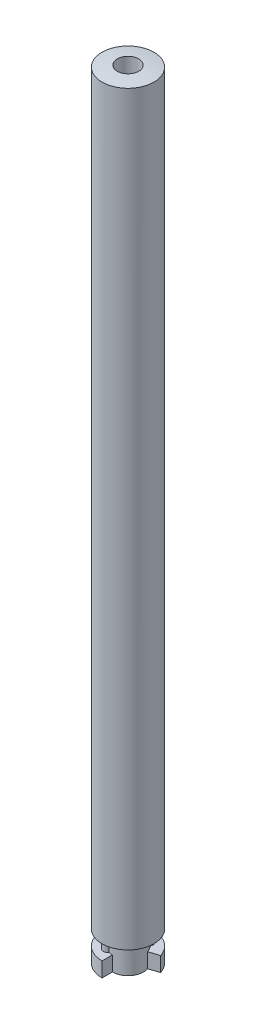
SolidWorks part; units mm, degrees
ref_plane "前视基准面" through (0, 0, 0) normal (0, 0, 1) x (1, 0, 0)
ref_plane "上视基准面" through (0, 0, 0) normal (0, 1, 0) x (1, 0, 0)
ref_plane "右视基准面" through (0, 0, 0) normal (1, 0, 0) x (0, 0, -1)
sketch "草图1" plane through (0, 0, 0) normal (0, 1, 0) x (1, 0, 0)
  circle A0 centre (0, 0) radius 3.5
  dimension "D1" = 7
extrude "凸台-拉伸1" add sketch "草图1" along normal blind 105
sketch "草图2" plane through (0, 0, 0) normal (0, -1, 0) x (1, 0, 0)
  line L0 (0, 0) -> (0, 3.5)
  line L1 (0, 0) -> (3.3287, -1.0816)
  line L2 (0, 3.5) -> (0, 2.1)
  line L3 (0, 0) -> (-3.3287, 1.0816)
  line L4 (0, 0) -> (0, -3.5)
  circle A0 centre (0, 0) radius 3.5 construction
  arc A1 (0, 3.5) -> (3.3287, -1.0816) centre (0, 0) cw
  arc A2 (1.9972, -0.6489) -> (0, 2.1) centre (0, 0) ccw
  arc A3 (0, -3.5) -> (-3.3287, 1.0816) centre (0, 0) cw
  arc A4 (-1.9972, 0.6489) -> (0, -2.1) centre (0, 0) ccw
  point P16 (0, 0)
  circle M1 centre (0, 0) radius 3.5
  dimension "D1" = 108
  dimension "D2" = 1.4
  dimension "D3" = 2
extrude "切除-拉伸1" cut sketch "草图2" against normal blind 2 contours A2 L1 L0 M1 | A4 L3 L4 M1
sketch "草图3" plane through (0, 2, 0) normal (0, -1, 0) x (1, 0, 0)
  circle A0 centre (0, 0) radius 3.5
  circle A1 centre (0, 0) radius 2.1
extrude "切除-拉伸3" cut sketch "草图3" against normal blind 2
sketch "草图4" plane through (0, 2, 0) normal (0, 1, 0) x (1, 0, 0)
  line L0 (-0.5435, -2.0284) -> (-0.9059, -3.3807) construction
  line L2 (0, -3.5) -> (0, -2.1)
  line L3 (-1.9972, -0.6489) -> (-3.3287, -1.0816)
  line L4 (0, -3.5) -> (0, -2.1)
  line L5 (-1.9972, -0.6489) -> (-3.3287, -1.0816)
  circle A0 centre (-0.5435, -2.0284) radius 0.5482 construction
  circle A1 centre (-1.026, -1.7681) radius 0.5482
  arc A2 (-3.3287, -1.0816) -> (0, -3.5) centre (0, 0) ccw
  arc A3 (-1.9972, -0.6489) -> (0, -2.1) centre (0, 0) ccw
  arc A4 (-3.3287, -1.0816) -> (0, -3.5) centre (0, 0) ccw
  arc A5 (-1.9972, -0.6489) -> (0, -2.1) centre (0, 0) ccw
  circle A6 centre (1.026, 1.7681) radius 0.5482
  point P16 (0, 0)
  arc M10 (0, -2.1) -> (-1.9972, -0.6489) centre (0, 0) cw
  dimension "D2" = 15
  dimension "D1" = 0
  dimension "D3" = 2
extrude "凸台-拉伸2" add sketch "草图4" along normal blind 2 contours A1 M10 | A6 | A1 M10
sketch "草图5" plane through (0, 105, 0) normal (0, 1, 0) x (1, 0, 0)
  circle A0 centre (0, 0) radius 1.45
  dimension "D1" = 2.9
extrude "切除-拉伸5" cut sketch "草图5" against normal blind 10
sketch "草图6" plane through (0, 0, 0) normal (0, 0, 1) x (1, 0, 0)
  line L0 (0, 107.6289) -> (0, 102.8466) construction
  line L1 (1.2031, 105) -> (1.2031, 104.9588)
  line L2 (3.5, 105) -> (3.5, 104.7)
  line L3 (3.5, 4) -> (3.5, 105) construction
  line L5 (3.5, 105) -> (1.2031, 105)
  spline S0 degree 3 poles (3.5, 104.7) (2.7379, 104.8257) (1.9723, 104.9119) (1.2031, 104.9588) knots 0 0 0 0 0.657832 0.657832 0.657832 0.657832
  dimension "D1" = 0.3
revolve "切除-旋转2" cut sketch "草图6" angle 360 about L0
